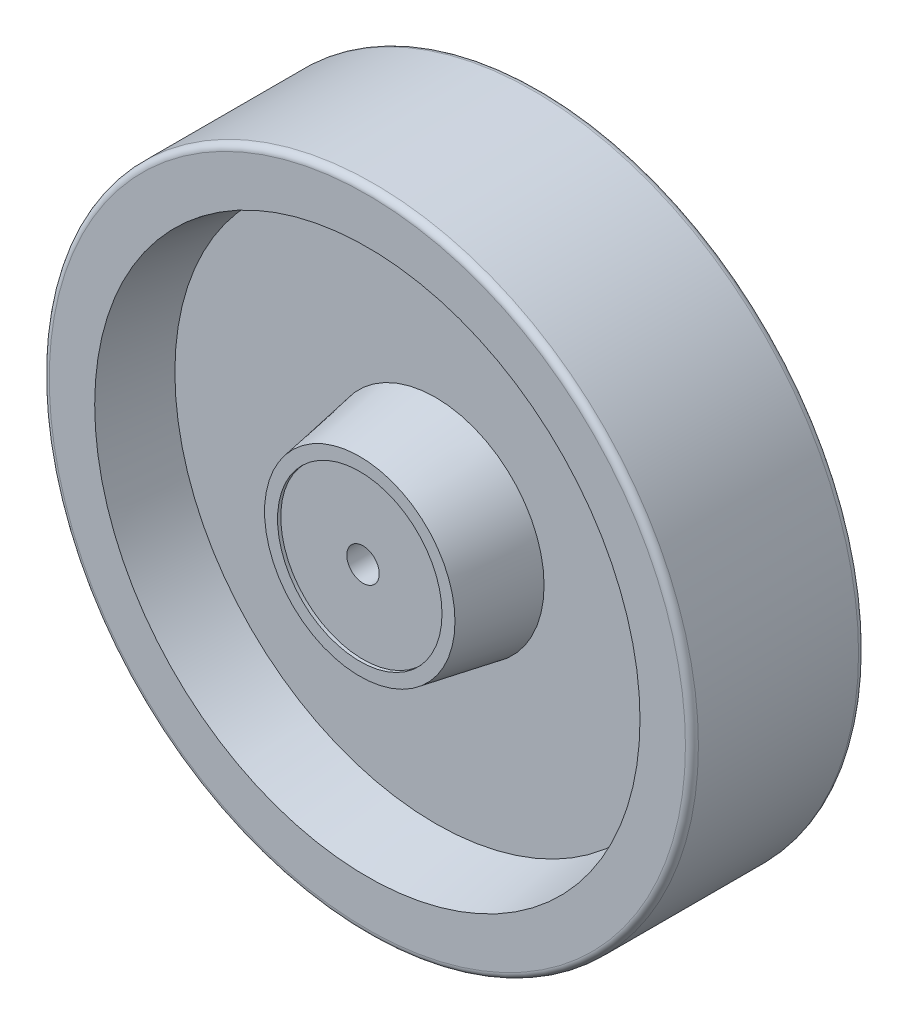
SolidWorks part; units mm, degrees
ref_plane "Front Plane" through (0, 0, 0) normal (0, 0, 1) x (1, 0, 0)
ref_plane "Top Plane" through (0, 0, 0) normal (0, 1, 0) x (1, 0, 0)
ref_plane "Right Plane" through (0, 0, 0) normal (1, 0, 0) x (0, 0, -1)
sketch "Sketch1" plane through (0, 0, 0) normal (0, 0, 1) x (1, 0, 0)
  circle A0 centre (0, 0) radius 150
  circle A1 centre (0, 0) radius 138
  dimension "D1" = 300
  dimension "D2" = 12
extrude "Boss-Extrude1" add sketch "Sketch1" along normal mid plane 80
fillet "Fillet1" radius 3 2 edges at (150, 0, -40) (150, 0, 40)
sketch "Sketch2" plane through (0, 0, 0) normal (0, 1, 0) x (1, 0, 0)
  line L0 (0, 0) -> (-182.8203, 0) construction
  line L1 (0, 0) -> (0, 99.8128) construction
  line L2 (0, 42) -> (0, -42)
  line L3 (0, -42) -> (-38, -42)
  line L4 (-38, -42) -> (-38, -43.5)
  line L5 (-38, -43.5) -> (-44, -43.5)
  line L6 (-44, -43.5) -> (-50.1714, -8.5)
  line L7 (-50.1714, -8.5) -> (-120.4457, -8.5)
  line L8 (-120.4457, -8.5) -> (-126, -40)
  line L9 (-126, -40) -> (-138, -40)
  line L10 (-138, -40) -> (-138, 40)
  line L11 (-147, -40) -> (147, -40) construction
  line L12 (-126, 40) -> (-138, 40)
  line L13 (-120.4457, 8.5) -> (-126, 40)
  line L14 (-50.1714, 8.5) -> (-120.4457, 8.5)
  line L15 (-44, 43.5) -> (-50.1714, 8.5)
  line L16 (-38, 43.5) -> (-44, 43.5)
  line L17 (-38, 42) -> (-38, 43.5)
  line L18 (0, 42) -> (-38, 42)
  point P2 (-41, -43.5)
  point P13 (-116.4947, -9.1131)
  point P15 (-126, -40)
  point P19 (-138, 0)
  dimension "D1" = 42
  dimension "D2" = 38
  dimension "D3" = 1.5
  dimension "D4" = 6
  dimension "D5" = 100
  dimension "D6" = 100
  dimension "D7" = 40
  dimension "D8" = 12
  dimension "D9" = 138
  dimension "D10" = 8.5
revolve "Revolve1" add sketch "Sketch2" angle 360 about L1
sketch "Sketch4" plane through (0, 0, 0) normal (0, 1, 0) x (1, 0, 0)
  line L0 (-36.6659, 28.5) -> (-36.6659, 8.5)
  line L1 (120.4457, 8.5) -> (-120.4457, 8.5) construction
  line L2 (-36.6659, 8.5) -> (-71.6659, 8.5)
  line L3 (-71.6659, 8.5) -> (-71.6659, 11.5)
  line L4 (-71.6659, 11.5) -> (-39.6659, 28.5)
  line L5 (-39.6659, 28.5) -> (-36.6659, 28.5)
  dimension "D1" = 20
  dimension "D2" = 35
  dimension "D3" = 3
  dimension "D4" = 3
extrude "Boss-Extrude2" add sketch "Sketch4" along normal mid plane 25
sketch "Sketch5" plane through (-20.5388, 0, -38.6613) normal (-0.4692, 0, -0.8831) x (-0.8831, 0, 0.4692)
  line L1 (49.8516, 3.4173) -> (43.4018, 7.754)
  line L2 (43.4018, 7.754) -> (36.4212, 4.3367)
  line L3 (36.4212, 4.3367) -> (35.8904, -3.4173)
  line L4 (35.8904, -3.4173) -> (42.3402, -7.754)
  line L5 (42.3402, -7.754) -> (49.3208, -4.3367)
  line L6 (49.3208, -4.3367) -> (49.8516, 3.4173)
  circle A0 centre (42.871, 0) radius 6.7309 construction
extrude "Boss-Extrude3" add sketch "Sketch5" along normal blind 5.5
sketch "Sketch6" plane through (-23.1192, 0, -43.5184) normal (-0.4692, 0, -0.8831) x (-0.8831, 0, 0.4692)
  line L0 (39.9115, 6.0454) -> (45.8305, -6.0454) construction
  line L1 (43.4018, 7.754) -> (36.4212, 4.3367) construction
  line L2 (42.3402, -7.754) -> (49.3208, -4.3367) construction
  circle A0 centre (42.871, 0) radius 6.7309
extrude "Boss-Extrude4" add sketch "Sketch6" along normal blind 3 draft 30
sketch "Sketch7" plane through (0, 0, 0) normal (0, 1, 0) x (1, 0, 0)
  line L0 (-62.3867, 26.0546) -> (-66.5054, 33.4717)
  line L1 (-62.3867, 26.0546) -> (-57.9721, 28.3998)
  line L3 (-62.3867, 26.0546) -> (-72.5486, 44.3544) construction
  arc A2 (-66.5054, 33.4717) -> (-57.9721, 28.3998) centre (-63.7165, 28.4494) cw
  point P3 (-62.3867, 26.0546)
  point P7 (0, 0)
revolve "Revolve3" add sketch "Sketch7" angle 360 about L3
sketch "Sketch8" plane through (0, 0, -42) normal (0, 0, -1) x (-1, 0, 0)
  circle A0 centre (0, 0) radius 7.5
  dimension "D1" = 15
extrude "Cut-Extrude1" cut sketch "Sketch8" against normal through all
